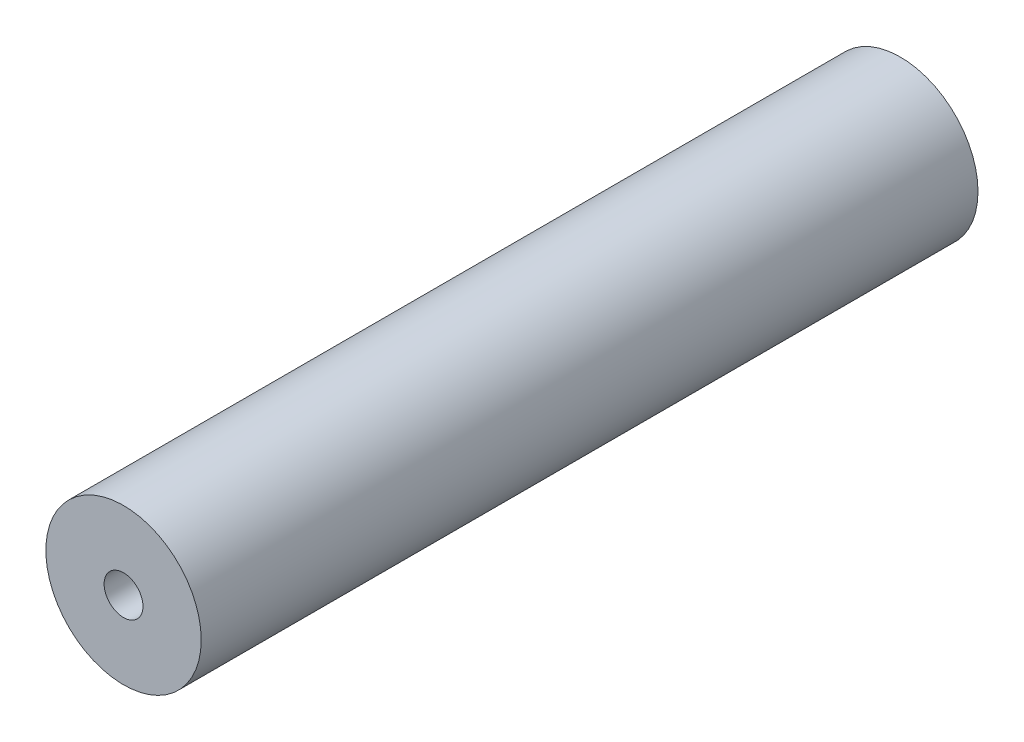
SolidWorks part; units mm, degrees
ref_plane "Front Plane" through (0, 0, 0) normal (0, 0, 1) x (1, 0, 0)
ref_plane "Top Plane" through (0, 0, 0) normal (0, 1, 0) x (1, 0, 0)
ref_plane "Right Plane" through (0, 0, 0) normal (1, 0, 0) x (0, 0, -1)
sketch "Sketch1" plane through (0, 0, 0) normal (0, 0, 1) x (1, 0, 0)
  circle A0 centre (0, 0) radius 25.4
  point P3 (0, 0)
  dimension "D1" = 50.8
extrude "Boss-Extrude1" add sketch "Sketch1" along normal blind 254
sketch "Sketch2" plane through (0, 0, 254) normal (0, 0, 1) x (1, 0, 0)
  circle A0 centre (0, 0) radius 6.35
  point P3 (0, 0)
  dimension "D1" = 12.7
extrude "Cut-Extrude1" cut sketch "Sketch2" against normal through all
